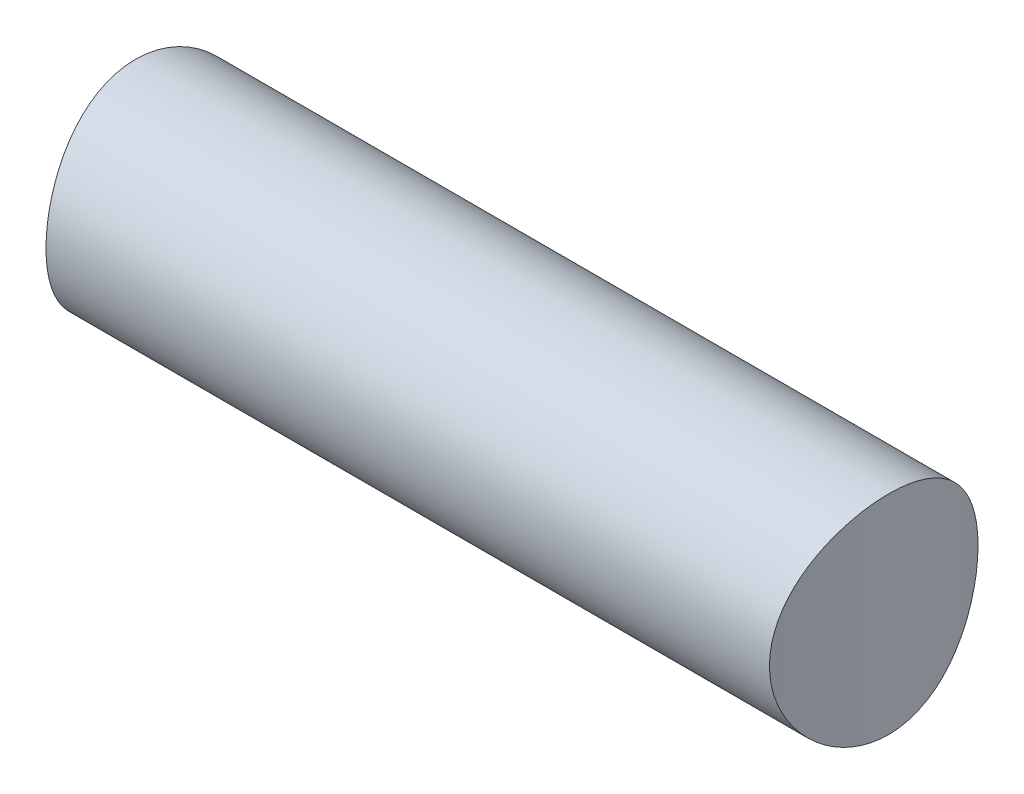
SolidWorks part; units mm, degrees
ref_plane "Alzado" through (0, 0, 0) normal (0, 0, 1) x (1, 0, 0)
ref_plane "Planta" through (0, 0, 0) normal (0, 1, 0) x (1, 0, 0)
ref_plane "Vista lateral" through (0, 0, 0) normal (1, 0, 0) x (0, 0, -1)
sketch "Croquis3" plane through (0, 0, 0) normal (0, 1, 0) x (1, 0, 0)
  circle A0 centre (0, 0) radius 6.86
  dimension "D1" = 13.72
extrude "Saliente-Extruir2" add sketch "Croquis3" along normal blind 10
sketch "Croquis4" plane through (0, 0, 0) normal (1, 0, 0) x (0, 0, -1)
  line L0 (0, 11.4001) -> (0, -1.6879) construction
  line L1 (-8.977, 6) -> (10.5976, 6) construction
  line L2 (6.86, 10) -> (-6.86, 10) construction
  circle A0 centre (0, 6) radius 1.9
  dimension "D2" = 3.8
  dimension "D1" = 4
extrude "Cortar-Extruir2" cut sketch "Croquis4" against normal through all both and the other way through all flip side to cut
